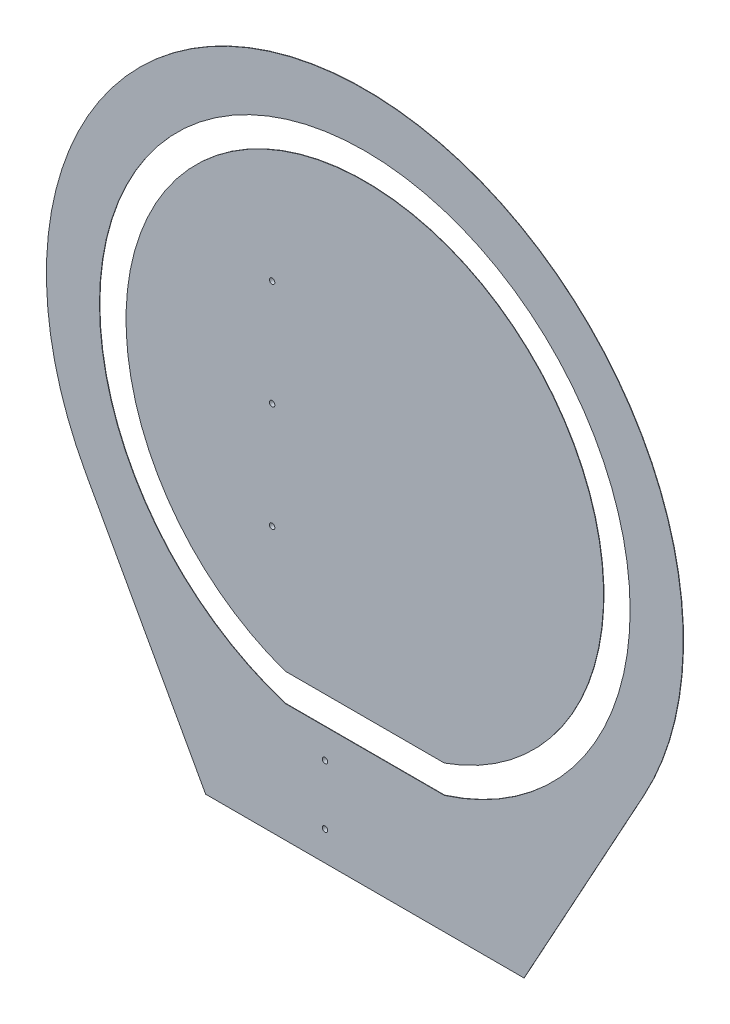
SolidWorks part; units mm, degrees
ref_plane "Plano frontal" through (0, 0, 0) normal (0, 0, 1) x (1, 0, 0)
ref_plane "Plano superior" through (0, 0, 0) normal (0, 1, 0) x (1, 0, 0)
ref_plane "Plano direito" through (0, 0, 0) normal (1, 0, 0) x (0, 0, -1)
sketch "Sketch1" plane through (0, 0, 0) normal (0, 0, 1) x (1, 0, 0)
  line L4 (-7.5, -21.2132) -> (7.5, -21.2132)
  line L8 (-7.5, -23.8485) -> (7.5, -23.8485)
  line L9 (0, -23.8485) -> (0, -35)
  line L10 (-15, -35) -> (15, -35)
  line L12 (-7.5, -23.8485) -> (7.5, -23.8485)
  line L13 (15, -25.6868) -> (15, -25.9808)
  line L14 (-15, -35) -> (-26.2929, -14.4459)
  line L15 (15, -35) -> (26.2929, -14.4459)
  arc A0 (7.5, -21.2132) -> (-7.5, -21.2132) centre (0, 0) ccw
  arc A1 (7.5, -23.8485) -> (-7.5, -23.8485) centre (0, 0) ccw
  arc A2 (26.2929, -14.4459) -> (-26.2929, -14.4459) centre (0, 0) ccw
  point P11 (0, -35)
  dimension "D6" = 50
  dimension "D7" = 60
  dimension "D3" = 2.6353
  dimension "D4" = 11.1515
  dimension "D5" = 30
extrude "Boss-Extrude1" add sketch "Sketch1" along normal blind 0.0356
sketch "Sketch2" plane through (0, 0, 0.0356) normal (0, 0, 1) x (1, 0, 0)
  line L0 (0, 22.5) -> (0, -35)
  line L1 (-15, -35) -> (15, -35) construction
  line L2 (-22.5, 0) -> (0, 0)
  line L3 (-8.7338, -20.7357) -> (-8.7338, 20.7357)
  line L4 (0, -23.8485) -> (-7.5, -23.8485)
  line L5 (-7.5, -23.8485) -> (7.5, -23.8485) construction
  line L6 (-3.75, -23.8485) -> (-3.75, -35)
  arc A0 (7.5, -21.2132) -> (-7.5, -21.2132) centre (0, 0) ccw construction
  circle A1 centre (-8.7338, 0) radius 0.254
  circle A2 centre (-8.7338, -10) radius 0.254
  circle A3 centre (-8.7338, 10) radius 0.254
  circle A4 centre (-3.75, -26.6242) radius 0.254
  circle A5 centre (-3.75, -32.2242) radius 0.254
  point P29 (-3.75, -29.4242)
  dimension "D1" = 0.508
  dimension "D2" = 0.508
  dimension "D3" = 0.508
  dimension "D8" = 0.508
  dimension "D9" = 0.508
  dimension "D4" = 10
  dimension "D5" = 10
  dimension "D6" = 2.8
  dimension "D7" = 2.8
extrude "Cut-Extrude1" cut sketch "Sketch2" against normal blind 10 contours L6 A5 | L6 A5 | L6 A4 | L6 A4 | L3 A2 | L3 A2 | A1 | A3
sketch "Esboço1" plane through (0, 0, 0) normal (0, 0, -1) x (-1, 0, 0)
  circle A0 centre (8.7338, 10) radius 0.2718
  circle A1 centre (8.7338, 10) radius 0.254
  circle A2 centre (8.7338, 0) radius 0.254
  circle A3 centre (8.7338, 0) radius 0.2718
  circle A4 centre (8.7338, -10) radius 0.254
  circle A5 centre (8.7338, -10) radius 0.2718
  circle A6 centre (3.75, -26.6242) radius 0.254
  circle A7 centre (3.75, -26.6242) radius 0.2718
  circle A8 centre (3.75, -32.2242) radius 0.254
  circle A9 centre (3.75, -32.2242) radius 0.2718
  dimension "D1" = 0.5436
  dimension "D2" = 0.5436
  dimension "D3" = 0.5436
  dimension "D4" = 0.5436
  dimension "D5" = 0.5436
extrude "Ressalto-extrusão1" add sketch "Esboço1" along normal blind 0.7544
